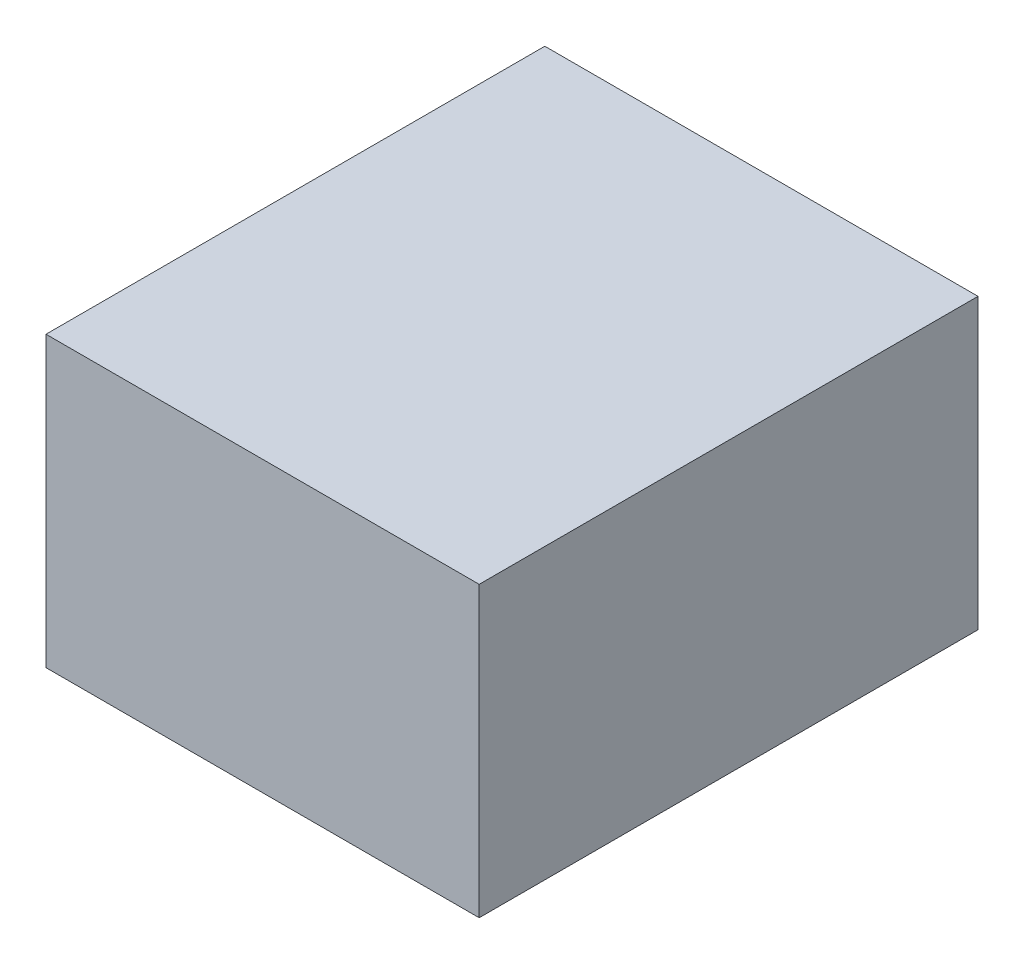
SolidWorks part; units mm, degrees
ref_plane "Front Plane" through (0, 0, 0) normal (0, 0, 1) x (1, 0, 0)
ref_plane "Top Plane" through (0, 0, 0) normal (0, 1, 0) x (1, 0, 0)
ref_plane "Right Plane" through (0, 0, 0) normal (1, 0, 0) x (0, 0, -1)
sketch "Sketch1" plane through (0, 0, 0) normal (0, 1, 0) x (1, 0, 0)
  line L1 (-209.55, -241.3) -> (209.55, -241.3)
  line L2 (-209.55, -241.3) -> (-209.55, 241.3)
  line L3 (-209.55, 241.3) -> (209.55, 241.3)
  line L4 (209.55, -241.3) -> (209.55, 241.3)
  line L5 (-209.55, -241.3) -> (209.55, 241.3) construction
  line L6 (-209.55, 241.3) -> (209.55, -241.3) construction
  point P0 (0, 0)
  dimension "D1" = 419.1
  dimension "D2" = 482.6
extrude "Boss-Extrude1" add sketch "Sketch1" along normal blind 279.4
